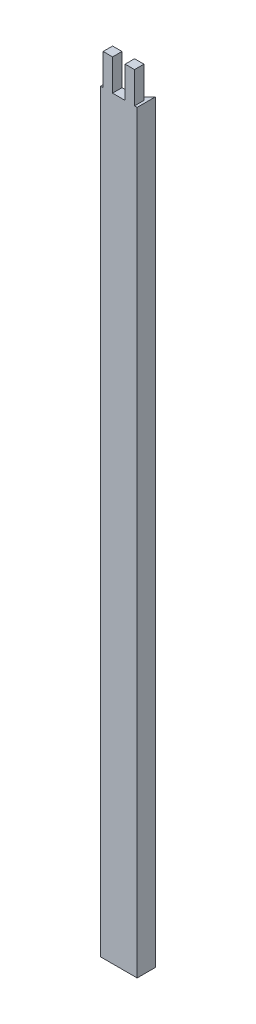
SolidWorks part; units mm, degrees
ref_plane "Front Plane" through (0, 0, 0) normal (0, 0, 1) x (1, 0, 0)
ref_plane "Top Plane" through (0, 0, 0) normal (0, 1, 0) x (1, 0, 0)
ref_plane "Right Plane" through (0, 0, 0) normal (1, 0, 0) x (0, 0, -1)
sketch "Sketch2" plane through (0, 0, 0) normal (0, 0, 1) x (1, 0, 0)
  line L1 (0, 0) -> (-6, 0)
  line L2 (0, 0) -> (0, -240)
  line L3 (0, -240) -> (-6, -240)
  line L4 (-6, 0) -> (-6, -240)
  dimension "D1" = 6
  dimension "D2" = 240
extrude "Boss-Extrude1" add sketch "Sketch2" along normal blind 3
sketch "Sketch4" plane through (0, -240, 0) normal (0, -1, 0) x (-1, 0, 0)
  line L0 (0, 0) -> (-2.8284, 2.8284)
  line L1 (-2.8284, 2.8284) -> (-2.8284, -3)
  line L2 (-2.8284, -3) -> (0, -3)
  line L3 (0, -3) -> (0, 0)
  line L4 (3, 0) -> (3, -3.7119) construction
  line L5 (6, 0) -> (0, 0) construction
  line L6 (8.8284, -3) -> (6, -3)
  line L7 (8.8284, 2.8284) -> (8.8284, -3)
  line L8 (6, 0) -> (8.8284, 2.8284)
  line L9 (6, -3) -> (6, 0)
  dimension "D1" = 135
  dimension "D2" = 4
extrude "Boss-Extrude2" add sketch "Sketch4" against normal up to vertex (240 mm away)
sketch "Sketch5" plane through (0, 0, 0) normal (0, 1, 0) x (1, 0, 0)
  line L0 (2.8284, -3) -> (-8.8284, -3) construction
  line L1 (-8, -3) -> (-5, -3)
  line L2 (-8, -3) -> (-8, 0)
  line L3 (-8, 0) -> (-5, 0)
  line L4 (-5, -3) -> (-5, 0)
  line L5 (-3, 0) -> (-3, -4.0355) construction
  line L6 (0, 0) -> (-6, 0) construction
  line L7 (2, 0) -> (-1, 0)
  line L8 (-1, -3) -> (-1, 0)
  line L9 (2, -3) -> (-1, -3)
  line L10 (2, -3) -> (2, 0)
  dimension "D1" = 3
  dimension "D2" = 2
  dimension "D3" = 0
extrude "Boss-Extrude3" add sketch "Sketch5" along normal blind 10
